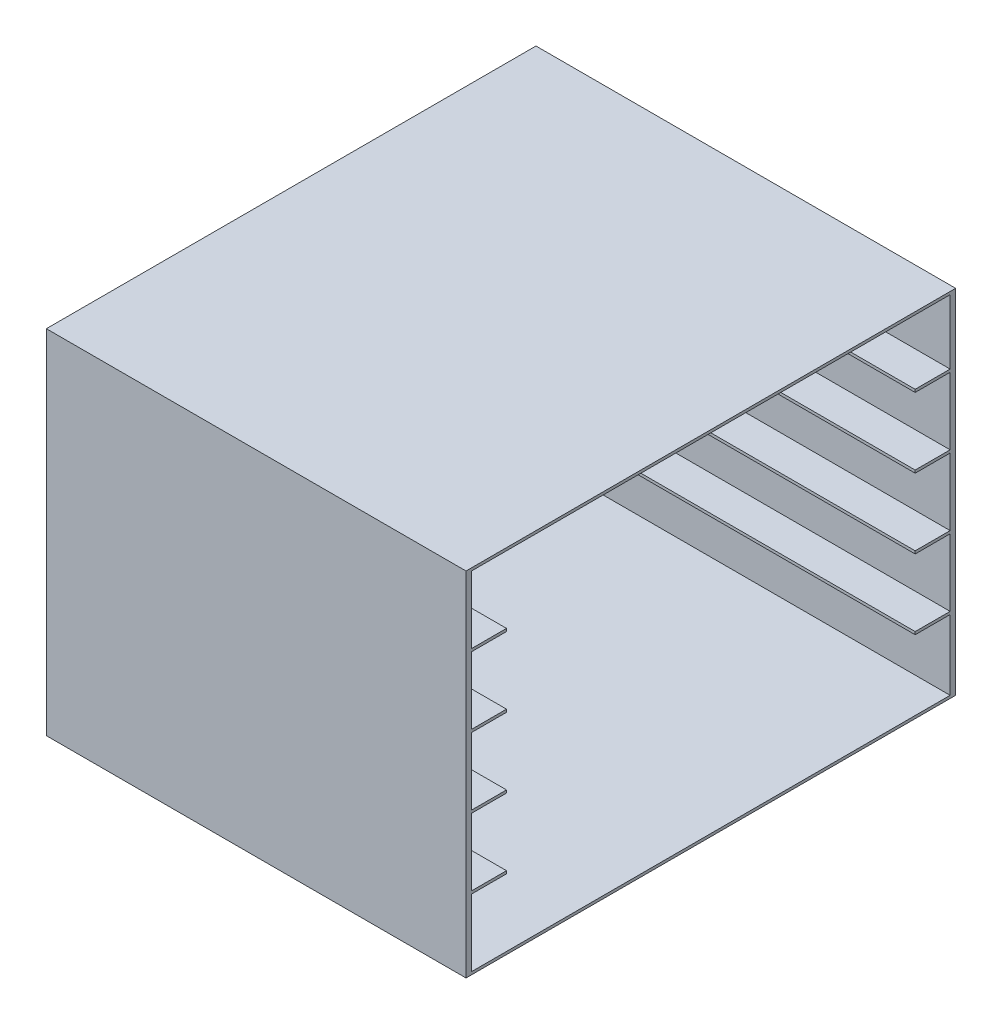
SolidWorks part; units mm, degrees
ref_plane "Front Plane" through (0, 0, 0) normal (0, 0, 1) x (1, 0, 0)
ref_plane "Top Plane" through (0, 0, 0) normal (0, 1, 0) x (1, 0, 0)
ref_plane "Right Plane" through (0, 0, 0) normal (1, 0, 0) x (0, 0, -1)
sketch "Sketch1" plane through (0, 0, 0) normal (0, 1, 0) x (1, 0, 0)
  line L1 (-76.2, -88.9) -> (76.2, -88.9)
  line L2 (-76.2, -88.9) -> (-76.2, 88.9)
  line L3 (-76.2, 88.9) -> (76.2, 88.9)
  line L4 (76.2, -88.9) -> (76.2, 88.9)
  line L5 (-76.2, -88.9) -> (76.2, 88.9) construction
  line L6 (-76.2, 88.9) -> (76.2, -88.9) construction
  point P0 (0, 0)
  dimension "D1" = 177.8
  dimension "D2" = 152.4
extrude "Boss-Extrude1" add sketch "Sketch1" along normal blind 1
sketch "Sketch15" plane through (0, 1, 0) normal (0, 1, 0) x (1, 0, 0)
  line L0 (76.2, -87.9) -> (-76.2, -87.9)
  line L1 (76.2, -88.9) -> (76.2, 88.9) construction
  line L2 (-76.2, 88.9) -> (-76.2, -88.9) construction
  line L3 (76.2, 87.9) -> (-76.2, 87.9)
  line L4 (-76.2, -88.9) -> (76.2, -88.9) construction
  line L5 (76.2, 88.9) -> (-76.2, 88.9) construction
  dimension "D1" = 1
  dimension "D2" = 1
extrude "Extrude-Thin1" add sketch "Sketch15" along normal blind 127 thin thin type two direction wall 1 second wall 1
sketch "Sketch16" plane through (0, 0, 86.9) normal (0, 0, -1) x (-1, 0, 0)
  line L0 (-76.2, 26.4) -> (76.2, 26.4)
  line L1 (-76.2, 128) -> (-76.2, 1) construction
  line L2 (76.2, 128) -> (76.2, 1) construction
  line L3 (-76.2, 1) -> (76.2, 1) construction
  line L4 (-76.2, 51.8) -> (76.2, 51.8)
  line L5 (-76.2, 77.2) -> (76.2, 77.2)
  line L6 (-76.2, 102.6) -> (76.2, 102.6)
  dimension "D1" = 25.4
extrude "Extrude-Thin2" add sketch "Sketch16" along normal blind 12.7 thin
sketch "Sketch17" plane through (0, 0, -86.9) normal (0, 0, 1) x (1, 0, 0)
  line L0 (76.2, 26.4) -> (-76.2, 26.4)
  line L1 (76.2, 128) -> (76.2, 1) construction
  line L2 (-76.2, 128) -> (-76.2, 1) construction
  line L3 (76.2, 1) -> (-76.2, 1) construction
  line L4 (76.2, 51.8) -> (-76.2, 51.8)
  line L5 (76.2, 77.2) -> (-76.2, 77.2)
  line L6 (76.2, 102.6) -> (-76.2, 102.6)
  dimension "D1" = 25.4
extrude "Extrude-Thin3" add sketch "Sketch17" along normal blind 12.7 thin
sketch "Sketch18" plane through (0, 0, 86.9) normal (0, 0, -1) x (-1, 0, 0)
  line L0 (-76.2, 128) -> (76.2, 128)
  line L1 (-76.2, 128) -> (-76.2, 102.6) construction
extrude "Extrude-Thin4" add sketch "Sketch18" along normal through all thin
